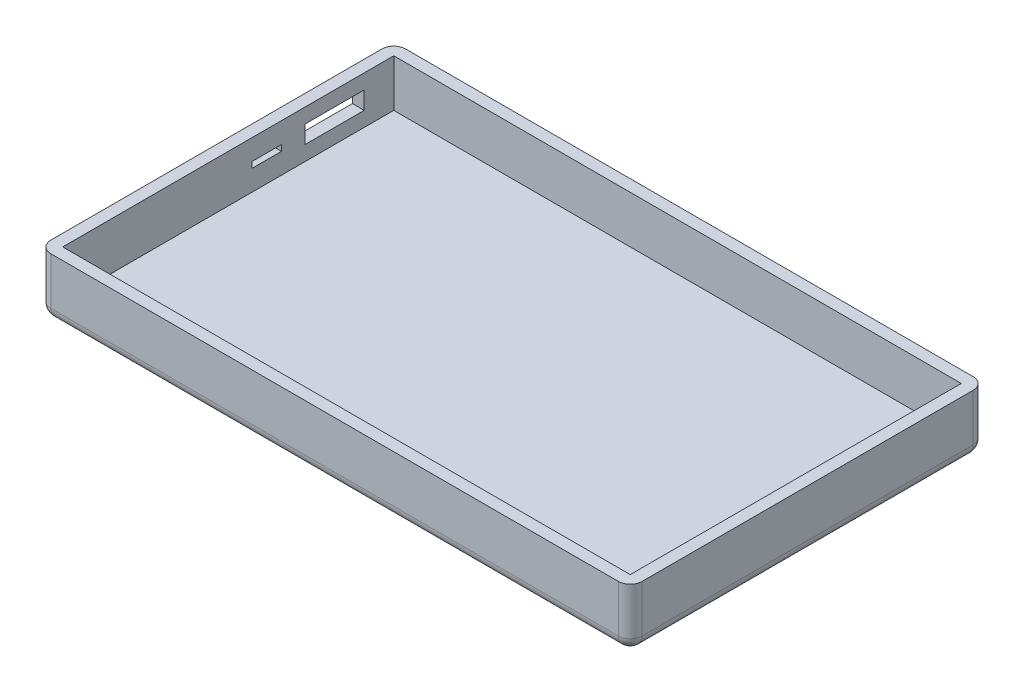
SolidWorks part; units mm, degrees
ref_plane "Front Plane" through (0, 0, 0) normal (0, 0, 1) x (1, 0, 0)
ref_plane "Top Plane" through (0, 0, 0) normal (0, 1, 0) x (1, 0, 0)
ref_plane "Right Plane" through (0, 0, 0) normal (1, 0, 0) x (0, 0, -1)
sketch "Sketch1" plane through (0, 0, 0) normal (0, 1, 0) x (1, 0, 0)
  line L1 (50, -30) -> (-50, -30)
  line L2 (50, -30) -> (50, 30)
  line L3 (50, 30) -> (-50, 30)
  line L4 (-50, -30) -> (-50, 30)
  line L5 (50, -30) -> (-50, 30) construction
  line L6 (50, 30) -> (-50, -30) construction
  point P0 (0, 0)
  dimension "D1" = 100
  dimension "D2" = 60
extrude "Boss-Extrude1" add sketch "Sketch1" along normal blind 10
shell "Shell1" thickness 2
fillet "Fillet1" radius 2 8 edges at (0, 0, 30) (-50, 5, 30) (-50, 0, 0) (-50, 5, -30) (0, 0, -30) (50, 5, -30) (50, 0, 0) (50, 5, 30)
sketch "Sketch2" plane through (-50, 0, 0) normal (-1, 0, 0) x (0, 0, 1)
  line L0 (-28, 10) -> (28, 10) construction
  line L1 (-9, 6.5) -> (-4, 6.5)
  line L2 (-9, 6.5) -> (-9, 5.5)
  line L3 (-9, 5.5) -> (-4, 5.5)
  line L4 (-4, 6.5) -> (-4, 5.5)
  line L5 (-9, 6.5) -> (-4, 5.5) construction
  line L6 (-9, 5.5) -> (-4, 6.5) construction
  line L7 (-13, 4.5) -> (-23, 4.5)
  line L8 (-13, 4.5) -> (-13, 7.5)
  line L9 (-13, 7.5) -> (-23, 7.5)
  line L10 (-23, 4.5) -> (-23, 7.5)
  line L11 (-13, 4.5) -> (-23, 7.5) construction
  line L12 (-13, 7.5) -> (-23, 4.5) construction
  line L13 (-28, 10) -> (-28, 2) construction
  point P0 (-6.5, 6)
  point P5 (-18, 6)
  dimension "D1" = 1
  dimension "D2" = 5
  dimension "D3" = 10
  dimension "D4" = 3
  dimension "D5" = 4
  dimension "D6" = 4
  dimension "D7" = 5
  dimension "D8" = 4
extrude "Cut-Extrude1" cut sketch "Sketch2" against normal up to surface (2 mm away) up to face at (-48, 6, 0)
